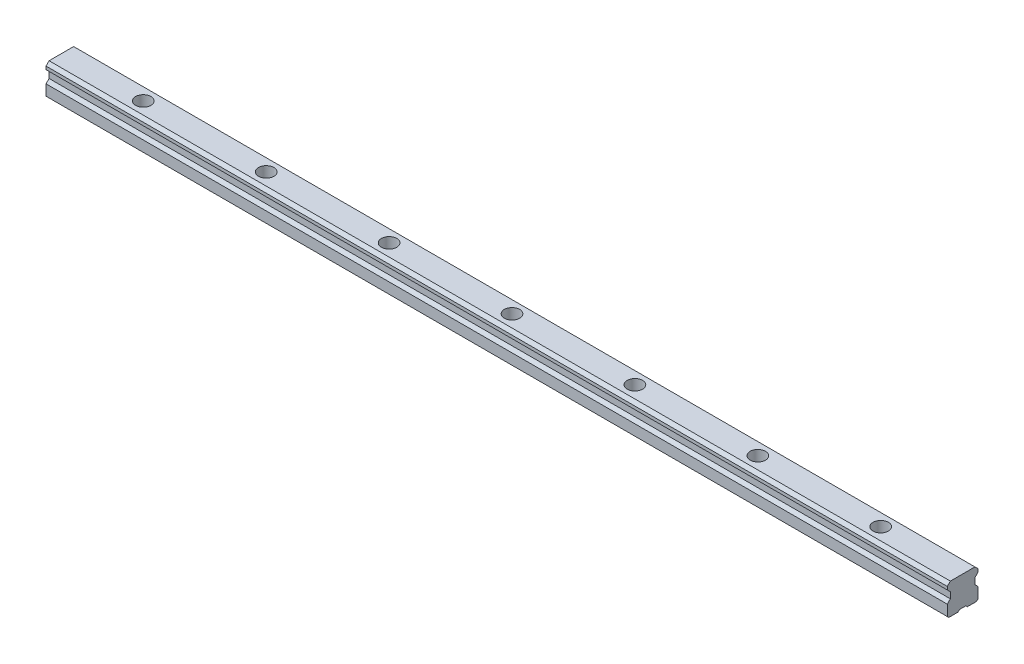
SolidWorks part; units mm, degrees
ref_plane "Front Plane" through (0, 0, 0) normal (0, 0, 1) x (1, 0, 0)
ref_plane "Top Plane" through (0, 0, 0) normal (0, 1, 0) x (1, 0, 0)
ref_plane "Right Plane" through (0, 0, 0) normal (1, 0, 0) x (0, 0, -1)
ref_plane "Plane1" through (250, 0, 0) normal (1, 0, 0) x (0, 0, -1)
sketch "Sketch1" plane through (250, 0, 0) normal (1, 0, 0) x (0, 0, -1)
  line L0 (-7.5, 6) -> (-7.5, 0)
  line L1 (-7.5, 0) -> (7.5, 0)
  line L2 (7.5, 0) -> (7.5, 6)
  line L3 (7.5, 6) -> (6, 7.5)
  line L4 (6, 7.5) -> (6, 10.5)
  line L5 (6, 10.5) -> (8.25, 12.75)
  line L6 (8.25, 12.75) -> (6, 15)
  line L7 (6, 15) -> (-6, 15)
  line L8 (-6, 15) -> (-8.25, 12.75)
  line L9 (-8.25, 12.75) -> (-6, 10.5)
  line L10 (-6, 10.5) -> (-6, 7.5)
  line L11 (-6, 7.5) -> (-7.5, 6)
extrude "Boss-Extrude1" add sketch "Sketch1" against normal blind 440
sketch "Sketch2" plane through (-190, 0, 0) normal (-1, 0, 0) x (0, 0, 1)
  line L0 (-2.25, 0) -> (2.25, 0)
  line L1 (2.25, 0) -> (1.5, 0.75)
  line L2 (1.5, 0.75) -> (-1.5, 0.75)
  line L3 (-1.5, 0.75) -> (-2.25, 0)
extrude "Cut-Extrude1" cut sketch "Sketch2" against normal through all
hole_wizard "CBORE for M4 Hex Head Machine Screw1" positions "Sketch4" profile "Sketch3" counterbore size "M4" standard "ANSI Metric"
sketch "Sketch4" plane through (0, 15, 0) normal (0, 1, 0) x (1, 0, 0)
  point P0 (210, 0)
  point P1 (150, 0)
  point P2 (90, 0)
  point P3 (30, 0)
  point P4 (-30, 0)
  point P5 (-90, 0)
  point P6 (-150, 0)
  point P7 (-210, 0)
sketch "Sketch3" plane through (210, 15, 0) normal (1, 0, 0) x (0, 0, 1)
  line L0 (0, 0) -> (0, 15)
  line L1 (0, 15) -> (2.25, 15)
  line L3 (2.25, 15) -> (2.25, 6)
  line L4 (2.25, 6) -> (3.75, 6)
  line L5 (3.75, 6) -> (3.75, 0)
  line L7 (3.75, 0) -> (0, 0)
  line L11 (0, -6.35) -> (0, 107.95) construction
  dimension "Thru Hole Dia." = 4.5
  dimension "Thru Hole Depth" = 15
  dimension "C'Bore Dia." = 7.5
  dimension "C'Bore Depth" = 6
chamfer "Chamfer1" distance 0.75 angle 45 2 edges at (30, 0, 7.5) (30, 0, -7.5)
chamfer "Chamfer2" distance 1.0607 angle 45 2 edges at (30, 12.75, 8.25) (30, 12.75, -8.25)
